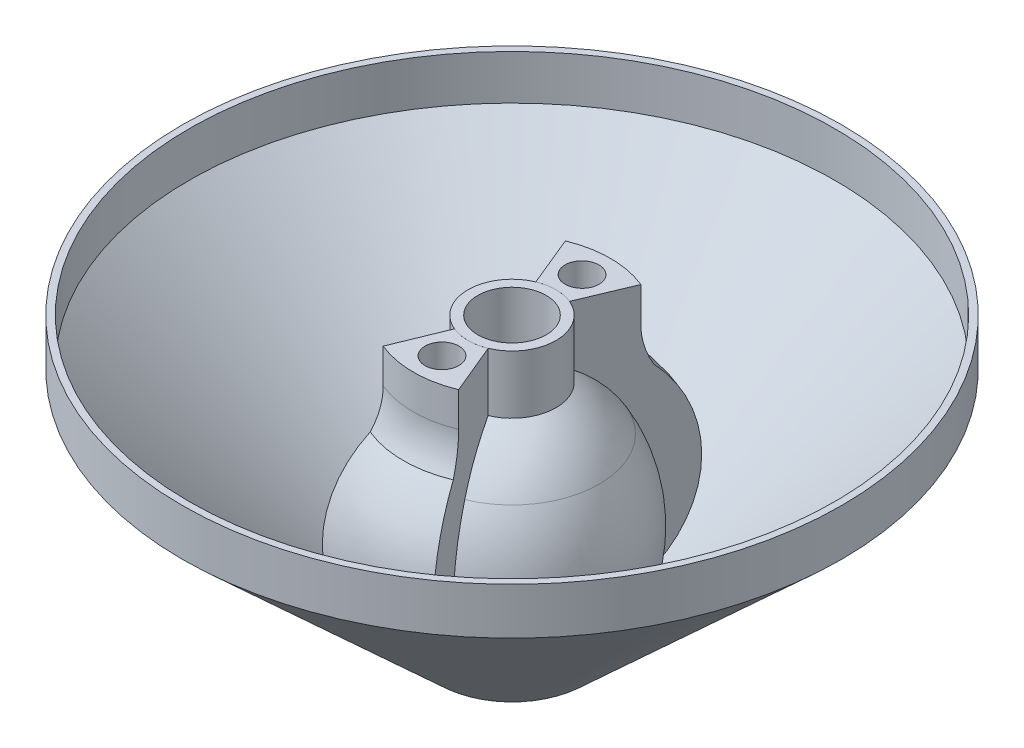
SolidWorks part; units mm, degrees
ref_plane "Front Plane" through (0, 0, 0) normal (0, 0, 1) x (1, 0, 0)
ref_plane "Top Plane" through (0, 0, 0) normal (0, 1, 0) x (1, 0, 0)
ref_plane "Right Plane" through (0, 0, 0) normal (1, 0, 0) x (0, 0, -1)
sketch "Sketch1" plane through (0, 0, 0) normal (1, 0, 0) x (0, 0, -1)
  line L0 (-48.729, 20.833) -> (-48.729, 13.9354)
  line L5 (-48.729, 20.833) -> (48.729, 20.833) construction
  line L6 (-48.729, 20.833) -> (-48.729, -20.833) construction
  line L7 (-48.729, -20.833) -> (48.729, -20.833) construction
  line L8 (48.729, 20.833) -> (48.729, -20.833) construction
  line L9 (-48.729, 20.833) -> (48.729, -20.833) construction
  line L10 (-48.729, -20.833) -> (48.729, 20.833) construction
  line L12 (-47.729, 20.833) -> (-47.729, 14.2217)
  line L16 (-47.729, 14.2217) -> (-27.0712, -18.8928) construction
  line L17 (-27.0712, -18.8928) -> (-12.9086, 5.6483) construction
  line L18 (-47.729, 20.833) -> (-48.729, 20.833)
  line L19 (0, 0) -> (0, -20.833) construction
  line L24 (-6.5023, 20.833) -> (-6.5023, 12.2224)
  line L29 (-5.0525, 20.833) -> (-6.5023, 20.833)
  line L30 (-5.0525, 20.833) -> (-5.0525, 11.8994)
  line L31 (-10.8682, -21.0027) -> (-48.729, 13.9354)
  line L32 (-16.1909, -15.5846) -> (-47.729, 14.2217)
  line L34 (-26.2044, -19.3915) -> (-12.0425, 5.1485) construction
  line L35 (-48.729, 13.9354) -> (-27.9212, -19.4195) construction
  arc A1 (-12.0425, 5.1485) -> (-5.0525, 11.8994) centre (3.2182, -3.6584) cw
  arc A2 (-12.9086, 5.6483) -> (-0.1361, 14.6565) centre (3.2182, -3.6584) cw construction
  arc A3 (-12.9086, 5.6483) -> (-6.5023, 12.2224) centre (3.2182, -3.6584) cw
  arc A5 (-27.0712, -18.8928) -> (-27.0712, -18.8928) centre (-27.0712, -18.8928) ccw construction
  arc A6 (-12.0425, 5.1485) -> (0.0441, 13.6729) centre (3.2182, -3.6584) cw construction
  arc A7 (-12.0425, 5.1485) -> (-10.0883, -20.3769) centre (7.597, -6.1854) ccw
  arc A8 (-12.9086, 5.6483) -> (-14.5678, -14.5064) centre (7.597, -6.1854) ccw
  arc A9 (-12.9086, 5.6483) -> (-10.8682, -21.0027) centre (7.597, -6.1854) ccw construction
  arc A10 (-16.1909, -15.5846) -> (-14.5678, -14.5064) centre (-15.504, -14.8579) ccw
  arc A11 (-10.0883, -20.3769) -> (-10.8682, -21.0027) centre (-10.7912, -20.2998) cw
  arc A12 (-27.9212, -19.4195) -> (-26.2044, -19.3915) centre (-27.0712, -18.8928) ccw construction
  point P0 (0, 0)
  point P14 (-27.0395, -20.833)
  point P22 (0, 0)
  point P24 (0, 0)
  point P40 (0, 0)
  dimension "D13" = 1
  dimension "D4" = 8.9336
  dimension "D5" = 8.6106
  dimension "D6" = 1.4498
  dimension "D7" = 6.6113
  dimension "D8" = 6.8976
  dimension "D9" = 41.2266
  dimension "D10" = 11.8994
  dimension "D11" = 5.0525
  dimension "D2" = 1
  dimension "D12" = 1
revolve "Revolve7" add sketch "Sketch1" angle 360 about L19
sketch "Sketch4" plane through (0, 0, 0) normal (1, 0, 0) x (0, 0, -1)
  line L5 (0, 0) -> (0, -20.833) construction
  line L9 (-14.5706, 15.7184) -> (-14.5706, 20.8073)
  line L10 (-14.5706, 20.8073) -> (-6.5023, 20.833)
  line L37 (-6.5023, 20.833) -> (-6.5023, 12.2224)
  line L60 (-6.5023, 20.833) -> (-6.5023, 12.2224)
  arc A5 (-12.9086, 5.6483) -> (-14.5678, -14.5064) centre (7.597, -6.1854) ccw
  arc A8 (-14.5706, 15.7184) -> (-16.0437, 10.2195) centre (-25.5706, 15.7184) cw
  arc A10 (-6.5023, 12.2224) -> (-12.9086, 5.6483) centre (3.2182, -3.6584) ccw
  arc A11 (-6.5023, 12.2224) -> (-12.9086, 5.6483) centre (3.2182, -3.6584) ccw
  arc A22 (-16.0437, 10.2195) -> (-16.1909, -15.5846) centre (-3.2152, -2.7562) ccw
  arc A44 (-6.5023, 12.2224) -> (-12.9086, 5.6483) centre (3.2182, -3.6584) ccw
  arc A45 (-12.9086, 5.6483) -> (-14.5678, -14.5064) centre (7.597, -6.1854) ccw
  arc A46 (-16.1909, -15.5846) -> (-14.5678, -14.5064) centre (-15.504, -14.8579) ccw
  dimension "D2" = 11
  dimension "D5" = 0
revolve "Revolve9" add sketch "Sketch4" angle 45 mid plane about L5
sketch "Sketch6" plane through (0, 0, 0) normal (1, 0, 0) x (0, 0, -1)
  line L1 (-7.7161, 12.2224) -> (-12.9455, 12.2224)
  arc A1 (-16.8001, -7.9134) -> (-17.6566, -9.2609) centre (-17.9021, -8.159) cw
  arc A2 (-7.7161, 12.2224) -> (-13.6908, 6.5893) centre (-2.3025, 0.4955) ccw
  spline S2 degree 3 poles (-104.1237, -2972.4991) (339.5784, 47.0224) (5.5604, 75.3765) (-16.2988, -0.3659) (-16.6325, -2.2203) (-16.9171, -5.9623) (-16.868, -7.8497) (-6.7317, -86.5605) (328.2325, -115.8657) (321.1104, 2946.2602) knots -10.053276 -10.053276 -10.053276 -10.053276 0.25 0.25 0.5 0.5 0.75 0.75 11.081194 11.081194 11.081194 11.081194 only from (-13.6908, 6.5893) to (-15.3485, -15.1618)
  spline S3 degree 3 poles (-13.6908, 6.5893) (-14.5612, 4.9567) (-15.2632, 3.2227) (-16.2988, -0.3659) (-16.6325, -2.2203) (-16.8715, -5.3624) (-16.8798, -6.641) (-16.8001, -7.9134) knots 0 0 0 0 0.25 0.25 0.5 0.5 0.66984 0.66984 0.66984 0.66984
  spline S4 degree 3 poles (247.4563, 2987.454) (-280.7406, -8.6368) (-23.9838, -32.4065) (-1.6071, 58.0049) (-239.6794, 172.9699) (-1081.3188, -2775.5704) knots -21.883448 -21.883448 -21.883448 -21.883448 0.5 0.5 23.04987 23.04987 23.04987 23.04987 only from (-13.9401, 9.7489) to (-12.4615, 15.7184)
  spline S5 degree 3 poles (-13.9401, 9.7489) (-13.5232, 10.5306) (-13.1892, 11.362) (-12.9455, 12.2224) knots 0 0 0 0 0.431854 0.431854 0.431854 0.431854
  spline S6 degree 3 poles (-1154.6714, -2750.0499) (277.265, -69.5722) (14.5699, 55.9886) (-16.67, 6.002) (-17.1702, 5.0032) (-17.9815, 2.917) (-18.2925, 1.8298) (-18.7127, -0.3906) (-18.8219, -1.5236) (-18.8338, -3.7911) (-18.7366, -4.9255) (-18.3398, -7.151) (-18.0402, -8.2421) (-17.2509, -10.3383) (-16.7612, -11.3434) (13.9413, -61.6984) (277.7949, 60.4601) (-1124.3385, 2757.1321) knots -6.429683 -6.429683 -6.429683 -6.429683 0.125 0.125 0.25 0.25 0.375 0.375 0.5 0.5 0.625 0.625 0.75 0.75 0.875 0.875 7.426892 7.426892 7.426892 7.426892 only from (-14.0918, 9.5367) to (-14.2201, -14.9102)
  spline S7 degree 3 poles (-13.9401, 9.7489) (-14.7505, 8.9058) (-15.4791, 7.968) (-16.6929, 6.019) (-17.1921, 5.0183) (-18.0009, 2.9288) (-18.3105, 1.84) (-18.7277, -0.3833) (-18.8352, -1.5176) (-18.8436, -3.7874) (-18.7445, -4.9228) (-18.3457, -7.1396) (-18.0478, -8.2213) (-17.6566, -9.2609) knots -0.00993 -0.00993 -0.00993 -0.00993 0.125 0.125 0.25 0.25 0.375 0.375 0.5 0.5 0.625 0.625 0.748837 0.748837 0.748837 0.748837
  dimension "D2" = 2
  dimension "D3" = 1
  dimension "D4" = 1
revolve "Cut-Revolve4" cut sketch "Sketch6" angle 30 mid plane about L19
ref_plane "Plane1" through (2.4988, 20.8329, 6.0327) normal (0.0012, 1, 0.0029) x (1, -0.0012, 0)
sketch "Sketch11" plane through (0.0047, 20.8537, 0.0115) normal (-0.0012, -1, -0.0029) x (1, -0.0012, 0)
  circle A1 centre (0.0207, 10.3662) radius 2.5
extrude "Cut-Extrude1" cut sketch "Sketch11" along normal blind 8.51
pattern_circular "CirPattern12" count 2 over 180 about axis through (0, 0, 0) along (0, -1, 0) of bodies 109 106
